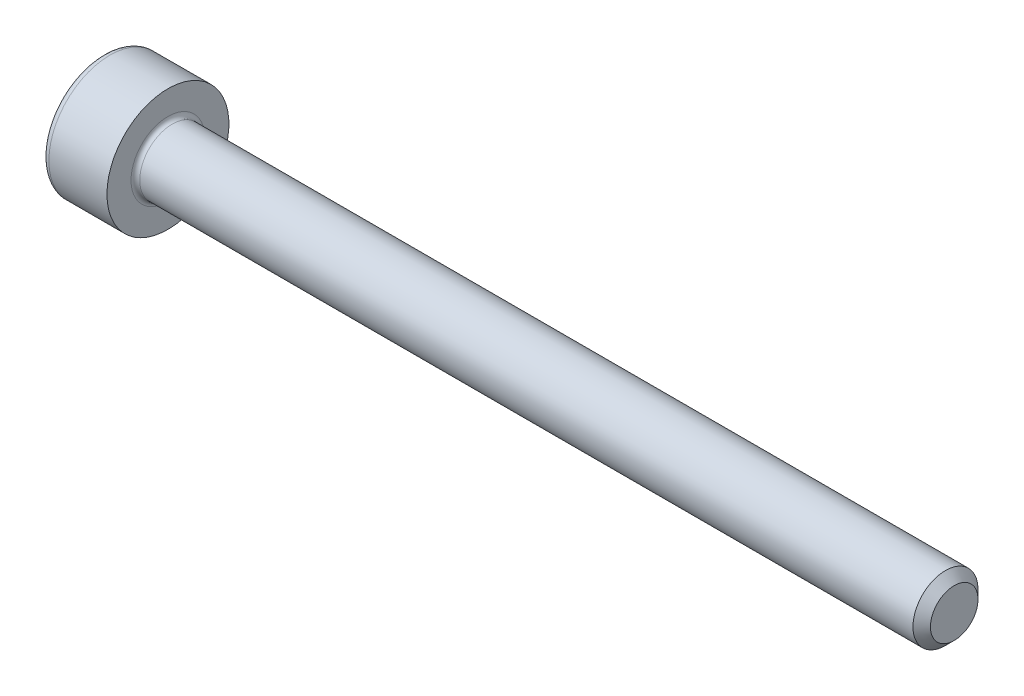
SolidWorks part; units mm, degrees
ref_plane "Спереди" through (0, 0, 0) normal (0, 0, 1) x (1, 0, 0)
ref_plane "Сверху" through (0, 0, 0) normal (0, 1, 0) x (1, 0, 0)
ref_plane "Справа" through (0, 0, 0) normal (1, 0, 0) x (0, 0, -1)
sketch "Sketch1" plane through (0, 0, 0) normal (0, 0, 1) x (1, 0, 0)
  line L0 (0, 0) -> (1.4887, 0)
  line L1 (1.4887, 0) -> (1.4887, 1.3957)
  line L2 (1.4887, 1.3957) -> (0, 1.3957)
  line L3 (0, 1.3957) -> (0, 0)
  line L4 (1.4887, 0) -> (19.4887, 0)
  line L5 (19.4887, 0) -> (19.4887, 0.7444)
  line L6 (19.4887, 0.7444) -> (1.4887, 0.7444)
  dimension "D1" = 18
revolve "Revolve1" add sketch "Sketch1" angle 360 about L0
fillet "Fillet1" radius 0.1 1 edges at (1.4887, 0, 0.7444)
fillet "Fillet2" radius 0.16 1 edges at (0, 0, 1.3957)
chamfer "Chamfer1" distance 0.2 angle 45 1 edges at (19.4887, 0, 0.7444)
sketch "Sketch2" plane through (0, 0, 0) normal (-1, 0, 0) x (0, 0, 1)
  line L1 (0, 0.8776) -> (-0.76, 0.4388)
  line L2 (-0.76, 0.4388) -> (-0.76, -0.4388)
  line L3 (-0.76, -0.4388) -> (0, -0.8776)
  line L4 (0, -0.8776) -> (0.76, -0.4388)
  line L5 (0.76, -0.4388) -> (0.76, 0.4388)
  line L6 (0.76, 0.4388) -> (0, 0.8776)
  circle A0 centre (0, 0) radius 0.76 construction
extrude "Extrude1" cut sketch "Sketch2" against normal blind 0.7
